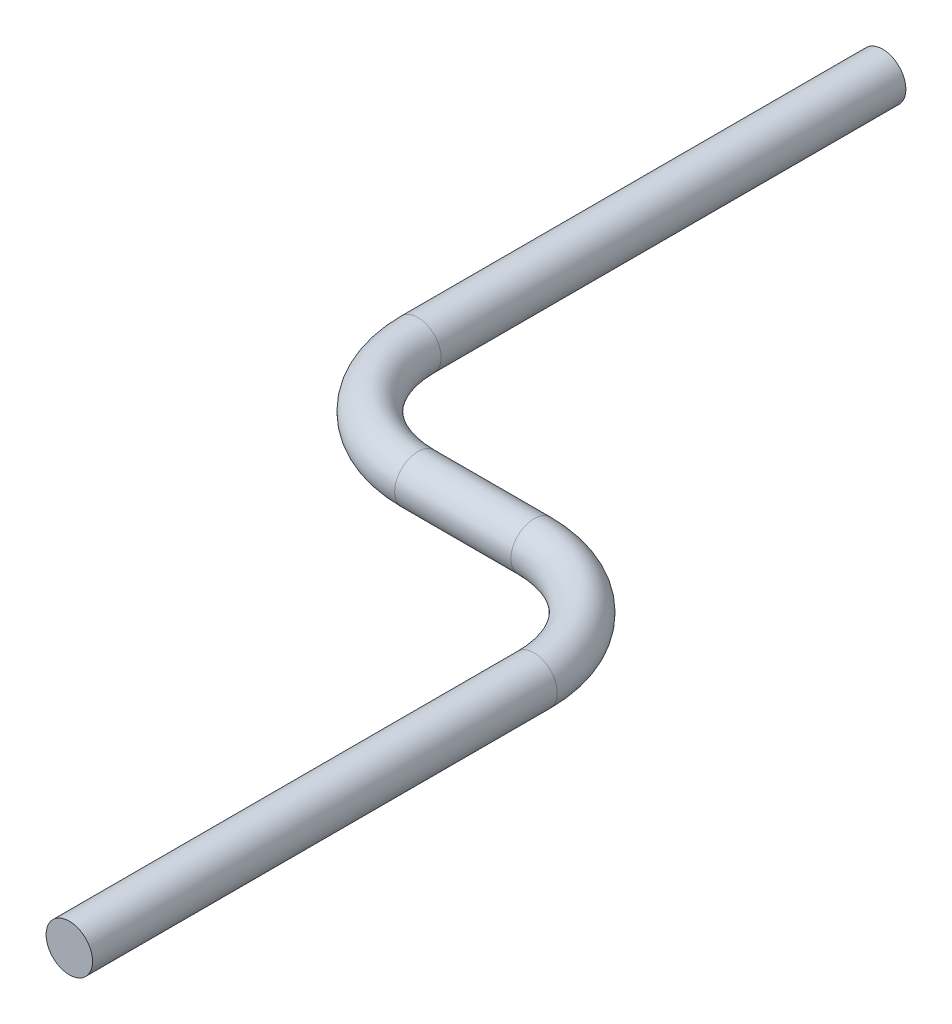
SolidWorks part; units mm, degrees
ref_plane "正面" through (0, 0, 0) normal (0, 0, 1) x (1, 0, 0)
ref_plane "平面" through (0, 0, 0) normal (0, 1, 0) x (1, 0, 0)
ref_plane "右側面" through (0, 0, 0) normal (1, 0, 0) x (0, 0, -1)
sketch "ｽｹｯﾁ1" plane through (0, 0, 0) normal (0, 0, 1) x (1, 0, 0)
  circle A0 centre (0, 0) radius 2
  dimension "D1" = 4
sketch "ｽｹｯﾁ2" plane through (0, 0, 0) normal (0, 1, 0) x (1, 0, 0)
  line L0 (0, 0) -> (0, -40)
  line L1 (10, -50) -> (20, -50)
  line L2 (30, -60) -> (30, -100)
  line L3 (-2, 0) -> (2, 0) construction
  line L4 (-2, 0) -> (2, 0)
  arc A0 (0, -40) -> (10, -50) centre (10, -40) ccw
  arc A1 (20, -50) -> (30, -60) centre (20, -60) cw
  dimension "D1" = 10
  dimension "D2" = 10
  dimension "D3" = 30
  dimension "D4" = 40
  dimension "D5" = 40
sweep "ｽｲｰﾌﾟ1" add profiles "ｽｹｯﾁ1" path "ｽｹｯﾁ2"
